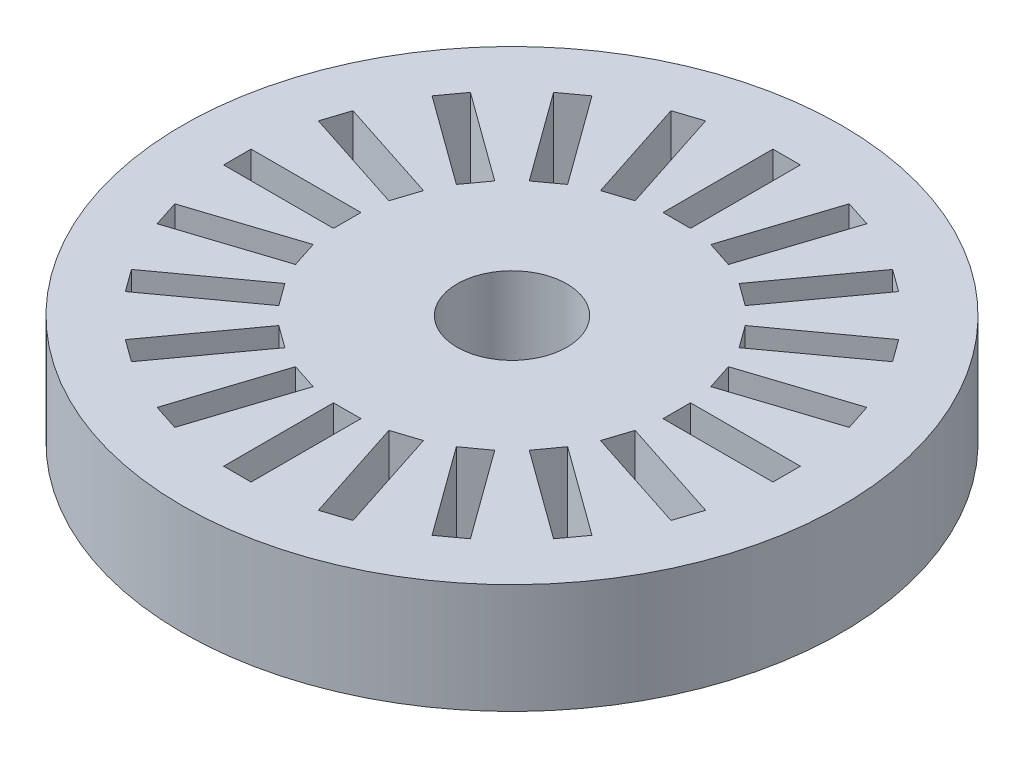
SolidWorks part; units mm, degrees
material "ABS PC"
ref_plane "Front Plane" through (0, 0, 0) normal (0, 0, 1) x (1, 0, 0)
ref_plane "Top Plane" through (0, 0, 0) normal (0, 1, 0) x (1, 0, 0)
ref_plane "Right Plane" through (0, 0, 0) normal (1, 0, 0) x (0, 0, -1)
sketch "Sketch1" plane through (0, 0, 0) normal (0, 1, 0) x (1, 0, 0)
  line L0 (3.0902, 9.5106) -> (2.6146, 9.6651)
  line L1 (2.6146, 9.6651) -> (1.3786, 5.8608)
  line L2 (0, 10) -> (-0.5, 10)
  line L3 (-0.5, 10) -> (-0.5, 6)
  line L4 (-0.5, 6) -> (0.5, 6)
  line L5 (0.5, 6) -> (0.5, 10)
  line L6 (0.5, 10) -> (0, 10)
  line L7 (0.5, 10) -> (-0.5, 10)
  line L8 (1.3786, 5.8608) -> (2.3296, 5.5518)
  line L9 (2.3296, 5.5518) -> (3.5657, 9.3561)
  line L10 (3.5657, 9.3561) -> (3.0902, 9.5106)
  line L11 (3.5657, 9.3561) -> (2.6146, 9.6651)
  line L12 (5.8779, 8.0902) -> (5.4733, 8.3841)
  line L13 (5.4733, 8.3841) -> (3.1222, 5.148)
  line L14 (3.1222, 5.148) -> (3.9312, 4.5602)
  line L15 (3.9312, 4.5602) -> (6.2824, 7.7963)
  line L16 (6.2824, 7.7963) -> (5.8779, 8.0902)
  line L17 (6.2824, 7.7963) -> (5.4733, 8.3841)
  line L18 (8.0902, 5.8779) -> (7.7963, 6.2824)
  line L19 (7.7963, 6.2824) -> (4.5602, 3.9312)
  line L20 (4.5602, 3.9312) -> (5.148, 3.1222)
  line L21 (5.148, 3.1222) -> (8.3841, 5.4733)
  line L22 (8.3841, 5.4733) -> (8.0902, 5.8779)
  line L23 (8.3841, 5.4733) -> (7.7963, 6.2824)
  line L24 (9.5106, 3.0902) -> (9.3561, 3.5657)
  line L25 (9.3561, 3.5657) -> (5.5518, 2.3296)
  line L26 (5.5518, 2.3296) -> (5.8608, 1.3786)
  line L27 (5.8608, 1.3786) -> (9.6651, 2.6146)
  line L28 (9.6651, 2.6146) -> (9.5106, 3.0902)
  line L29 (9.6651, 2.6146) -> (9.3561, 3.5657)
  line L30 (10, 0) -> (10, 0.5)
  line L31 (10, 0.5) -> (6, 0.5)
  line L32 (6, 0.5) -> (6, -0.5)
  line L33 (6, -0.5) -> (10, -0.5)
  line L34 (10, -0.5) -> (10, 0)
  line L35 (10, -0.5) -> (10, 0.5)
  line L36 (9.5106, -3.0902) -> (9.6651, -2.6146)
  line L37 (9.6651, -2.6146) -> (5.8608, -1.3786)
  line L38 (5.8608, -1.3786) -> (5.5518, -2.3296)
  line L39 (5.5518, -2.3296) -> (9.3561, -3.5657)
  line L40 (9.3561, -3.5657) -> (9.5106, -3.0902)
  line L41 (9.3561, -3.5657) -> (9.6651, -2.6146)
  line L42 (8.0902, -5.8779) -> (8.3841, -5.4733)
  line L43 (8.3841, -5.4733) -> (5.148, -3.1222)
  line L44 (5.148, -3.1222) -> (4.5602, -3.9312)
  line L45 (4.5602, -3.9312) -> (7.7963, -6.2824)
  line L46 (7.7963, -6.2824) -> (8.0902, -5.8779)
  line L47 (7.7963, -6.2824) -> (8.3841, -5.4733)
  line L48 (5.8779, -8.0902) -> (6.2824, -7.7963)
  line L49 (6.2824, -7.7963) -> (3.9312, -4.5602)
  line L50 (3.9312, -4.5602) -> (3.1222, -5.148)
  line L51 (3.1222, -5.148) -> (5.4733, -8.3841)
  line L52 (5.4733, -8.3841) -> (5.8779, -8.0902)
  line L53 (5.4733, -8.3841) -> (6.2824, -7.7963)
  line L54 (3.0902, -9.5106) -> (3.5657, -9.3561)
  line L55 (3.5657, -9.3561) -> (2.3296, -5.5518)
  line L56 (2.3296, -5.5518) -> (1.3786, -5.8608)
  line L57 (1.3786, -5.8608) -> (2.6146, -9.6651)
  line L58 (2.6146, -9.6651) -> (3.0902, -9.5106)
  line L59 (2.6146, -9.6651) -> (3.5657, -9.3561)
  line L60 (0, -10) -> (0.5, -10)
  line L61 (0.5, -10) -> (0.5, -6)
  line L62 (0.5, -6) -> (-0.5, -6)
  line L63 (-0.5, -6) -> (-0.5, -10)
  line L64 (-0.5, -10) -> (0, -10)
  line L65 (-0.5, -10) -> (0.5, -10)
  line L66 (-3.0902, -9.5106) -> (-2.6146, -9.6651)
  line L67 (-2.6146, -9.6651) -> (-1.3786, -5.8608)
  line L68 (-1.3786, -5.8608) -> (-2.3296, -5.5518)
  line L69 (-2.3296, -5.5518) -> (-3.5657, -9.3561)
  line L70 (-3.5657, -9.3561) -> (-3.0902, -9.5106)
  line L71 (-3.5657, -9.3561) -> (-2.6146, -9.6651)
  line L72 (-5.8779, -8.0902) -> (-5.4733, -8.3841)
  line L73 (-5.4733, -8.3841) -> (-3.1222, -5.148)
  line L74 (-3.1222, -5.148) -> (-3.9312, -4.5602)
  line L75 (-3.9312, -4.5602) -> (-6.2824, -7.7963)
  line L76 (-6.2824, -7.7963) -> (-5.8779, -8.0902)
  line L77 (-6.2824, -7.7963) -> (-5.4733, -8.3841)
  line L78 (-8.0902, -5.8779) -> (-7.7963, -6.2824)
  line L79 (-7.7963, -6.2824) -> (-4.5602, -3.9312)
  line L80 (-4.5602, -3.9312) -> (-5.148, -3.1222)
  line L81 (-5.148, -3.1222) -> (-8.3841, -5.4733)
  line L82 (-8.3841, -5.4733) -> (-8.0902, -5.8779)
  line L83 (-8.3841, -5.4733) -> (-7.7963, -6.2824)
  line L84 (-9.5106, -3.0902) -> (-9.3561, -3.5657)
  line L85 (-9.3561, -3.5657) -> (-5.5518, -2.3296)
  line L86 (-5.5518, -2.3296) -> (-5.8608, -1.3786)
  line L87 (-5.8608, -1.3786) -> (-9.6651, -2.6146)
  line L88 (-9.6651, -2.6146) -> (-9.5106, -3.0902)
  line L89 (-9.6651, -2.6146) -> (-9.3561, -3.5657)
  line L90 (-10, 0) -> (-10, -0.5)
  line L91 (-10, -0.5) -> (-6, -0.5)
  line L92 (-6, -0.5) -> (-6, 0.5)
  line L93 (-6, 0.5) -> (-10, 0.5)
  line L94 (-10, 0.5) -> (-10, 0)
  line L95 (-10, 0.5) -> (-10, -0.5)
  line L96 (-9.5106, 3.0902) -> (-9.6651, 2.6146)
  line L97 (-9.6651, 2.6146) -> (-5.8608, 1.3786)
  line L98 (-5.8608, 1.3786) -> (-5.5518, 2.3296)
  line L99 (-5.5518, 2.3296) -> (-9.3561, 3.5657)
  line L100 (-9.3561, 3.5657) -> (-9.5106, 3.0902)
  line L101 (-9.3561, 3.5657) -> (-9.6651, 2.6146)
  line L102 (-8.0902, 5.8779) -> (-8.3841, 5.4733)
  line L103 (-8.3841, 5.4733) -> (-5.148, 3.1222)
  line L104 (-5.148, 3.1222) -> (-4.5602, 3.9312)
  line L105 (-4.5602, 3.9312) -> (-7.7963, 6.2824)
  line L106 (-7.7963, 6.2824) -> (-8.0902, 5.8779)
  line L107 (-7.7963, 6.2824) -> (-8.3841, 5.4733)
  line L108 (-5.8779, 8.0902) -> (-6.2824, 7.7963)
  line L109 (-6.2824, 7.7963) -> (-3.9312, 4.5602)
  line L110 (-3.9312, 4.5602) -> (-3.1222, 5.148)
  line L111 (-3.1222, 5.148) -> (-5.4733, 8.3841)
  line L112 (-5.4733, 8.3841) -> (-5.8779, 8.0902)
  line L113 (-5.4733, 8.3841) -> (-6.2824, 7.7963)
  line L114 (-3.0902, 9.5106) -> (-3.5657, 9.3561)
  line L115 (-3.5657, 9.3561) -> (-2.3296, 5.5518)
  line L116 (-2.3296, 5.5518) -> (-1.3786, 5.8608)
  line L117 (-1.3786, 5.8608) -> (-2.6146, 9.6651)
  line L118 (-2.6146, 9.6651) -> (-3.0902, 9.5106)
  line L119 (-2.6146, 9.6651) -> (-3.5657, 9.3561)
  circle A0 centre (0, 0) radius 12
  circle A1 centre (0, 0) radius 2
  point P106 (0, 0)
  dimension "D1" = 20
extrude "Boss-Extrude1" add sketch "Sketch1" along normal blind 4 contours A0 A1 L6 L5 L4 L3 L2 L10 L9 L8 L1 L0 L16 L15 L14 L13 L12 L22 L21 L20 L19 L18 L28 L27 L26 L25 L24 L34 L33 L32 L31 L30 L40 L39 L38 L37 L36 L46 L45 L44 L43 L42
